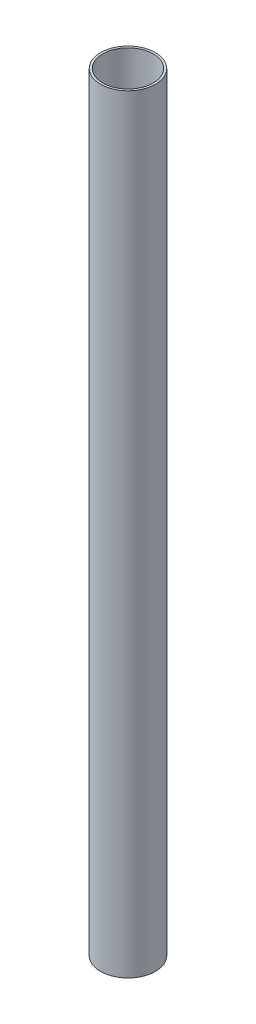
SolidWorks part; units mm, degrees
material "Thornel VCB-20 Carbon Cloth"
ref_plane "Front Plane" through (0, 0, 0) normal (0, 0, 1) x (1, 0, 0)
ref_plane "Top Plane" through (0, 0, 0) normal (0, 1, 0) x (1, 0, 0)
ref_plane "Right Plane" through (0, 0, 0) normal (1, 0, 0) x (0, 0, -1)
sketch "Sketch2" plane through (0, 0, 0) normal (0, 1, 0) x (1, 0, 0)
  circle A0 centre (0, 0) radius 12.5
  dimension "D1" = 25
extrude "Boss-Extrude1" add sketch "Sketch2" along normal blind 350 contours A0
sketch "Sketch4" plane through (0, 0, 0) normal (0, -1, 0) x (1, 0, 0)
  circle A0 centre (0, 0) radius 11.5
  dimension "D1" = 23
extrude "Cut-Extrude1" cut sketch "Sketch4" against normal through all
